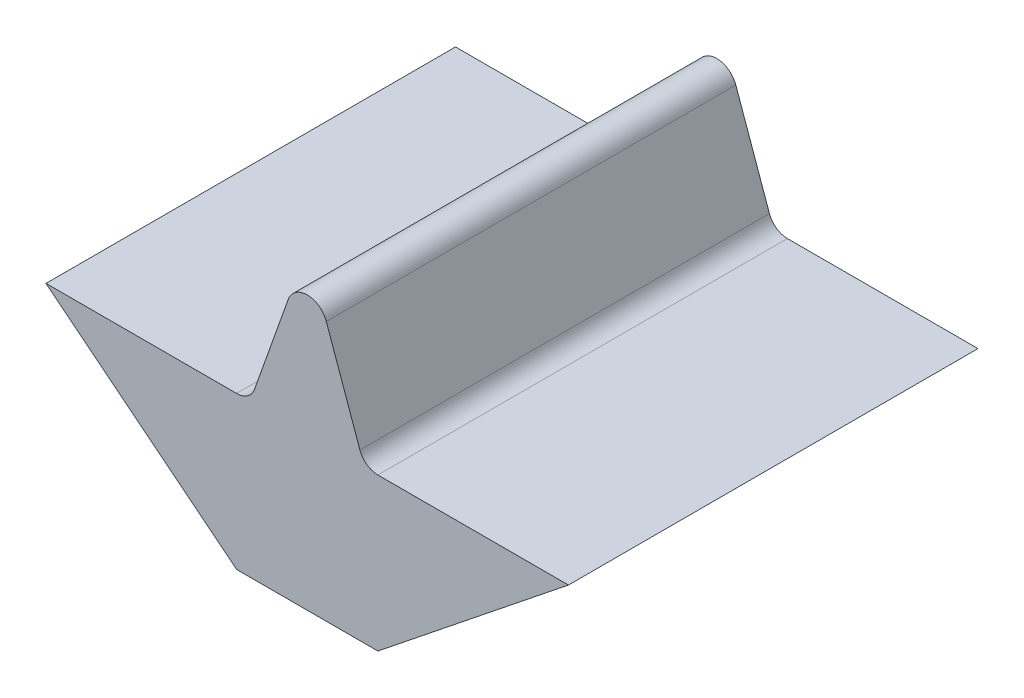
SolidWorks part; units mm, degrees
material "NEOPRENE"
ref_plane "Front Plane" through (0, 0, 0) normal (0, 0, 1) x (1, 0, 0)
ref_plane "Top Plane" through (0, 0, 0) normal (0, 1, 0) x (1, 0, 0)
ref_plane "Right Plane" through (0, 0, 0) normal (1, 0, 0) x (0, 0, -1)
sketch "Sketch1" plane through (0, 0, 0) normal (0, 0, 1) x (1, 0, 0)
  line L0 (401.25, 0) -> (-401.25, 0) construction
  line L1 (401.25, 0) -> (601.25, 200) construction
  line L2 (601.25, 200) -> (-601.25, 200) construction
  line L3 (-601.25, 200) -> (-401.25, 0) construction
  line L4 (-601.25, 283.4375) -> (601.25, 283.4375)
  line L5 (660.2492, 141.0008) -> (460.2492, -58.9992)
  line L6 (-401.25, -83.4375) -> (401.25, -83.4375)
  line L7 (-460.2492, -58.9992) -> (-660.2492, 141.0008)
  line L8 (-601.25, 303.4375) -> (-18.0902, 303.4375) construction
  line L9 (674.3914, 126.8586) -> (474.3914, -73.1414) construction
  line L10 (401.25, -103.4375) -> (-401.25, -103.4375) construction
  line L11 (-474.3914, -73.1414) -> (-674.3914, 126.8586) construction
  line L12 (0, 0) -> (0, 487.9759) construction
  line L13 (-13.618, 306.2014) -> (-5, 323.4375)
  line L15 (5, 323.4375) -> (13.618, 306.2014)
  line L16 (18.0902, 303.4375) -> (601.25, 303.4375) construction
  line L17 (-289.7519, 525.3669) -> (-115.2952, 525.3669)
  arc A0 (-601.25, 283.4375) -> (-660.2492, 141.0008) centre (-601.25, 200) ccw
  arc A1 (660.2492, 141.0008) -> (601.25, 283.4375) centre (601.25, 200) ccw
  arc A2 (401.25, -83.4375) -> (460.2492, -58.9992) centre (401.25, 0) ccw
  arc A3 (-460.2492, -58.9992) -> (-401.25, -83.4375) centre (-401.25, 0) ccw
  arc A5 (-601.25, 303.4375) -> (-674.3914, 126.8586) centre (-601.25, 200) ccw construction
  arc A6 (674.3914, 126.8586) -> (601.25, 303.4375) centre (601.25, 200) ccw construction
  arc A7 (401.25, -103.4375) -> (474.3914, -73.1414) centre (401.25, 0) ccw construction
  arc A8 (-474.3914, -73.1414) -> (-401.25, -103.4375) centre (-401.25, 0) ccw construction
  arc A9 (13.618, 306.2014) -> (18.0902, 303.4375) centre (18.0902, 308.4375) ccw
  arc A10 (-13.618, 306.2014) -> (-18.0902, 303.4375) centre (-18.0902, 308.4375) cw
  arc A11 (-5, 323.4375) -> (5, 323.4375) centre (0, 320.9375) cw
  spline S0 degree 3 poles (18.0902, 303.4375) (212.4768, 303.4375) (413.5359, 303.4375) (621.2675, 303.4375) (641.3554, 296.0526) (653.1688, 289.7122) (658.7168, 286.0051) (694.6034, 262.0265) (711.1202, 222.1515) (702.7, 179.8203) (701.3982, 173.276) (697.5283, 160.4393) (688.5459, 141.0132) (612.4429, 64.9102) (539.4649, -8.0678) (469.612, -77.9208) (464.255, -82.1276) (460.5901, -84.7534) (458.7168, -86.0051) (447.3858, -93.5763) (434.7955, -98.7914) (421.4297, -101.45) (419.2199, -101.8895) (414.7717, -102.6242) (408.0091, -103.4375) (136.003, -103.4375) (-136.003, -103.4375) (-408.0091, -103.4375) (-414.7717, -102.6242) (-419.2199, -101.8895) (-421.4297, -101.45) (-434.7955, -98.7914) (-447.3858, -93.5763) (-458.7168, -86.0051) (-460.5901, -84.7534) (-464.255, -82.1276) (-469.612, -77.9208) (-539.4649, -8.0678) (-612.4429, 64.9102) (-688.5459, 141.0132) (-697.5283, 160.4393) (-701.3982, 173.276) (-702.7, 179.8203) (-711.1202, 222.1515) (-694.6034, 262.0265) (-658.7168, 286.0051) (-653.1688, 289.7122) (-641.3554, 296.0526) (-621.2675, 303.4375) (-413.5359, 303.4375) (-212.4768, 303.4375) (-18.0902, 303.4375) knots 0 0 0 0 0.184171 0.190492 0.196814 0.203136 0.203136 0.203136 0.239434 0.239434 0.239434 0.245756 0.252078 0.258399 0.347725 0.34986 0.351995 0.354129 0.354129 0.354129 0.366875 0.366875 0.366875 0.36901 0.371145 0.373279 0.626721 0.628855 0.63099 0.633125 0.633125 0.633125 0.645871 0.645871 0.645871 0.648005 0.65014 0.652275 0.741601 0.747922 0.754244 0.760566 0.760566 0.760566 0.796864 0.796864 0.796864 0.803186 0.809508 0.815829 1 1 1 1 weights 1 1 1 1 1 1 1 0.887646 0.887646 1 1 1 1 1 1 1 1 1 1 0.98719 0.98719 1 1 1 1 1 1 1 1 1 1 0.98719 0.98719 1 1 1 1 1 1 1 1 1 1 0.887646 0.887646 1 1 1 1 1 1 1
  point P4 (0, 0)
  point P37 (15, 303.4375)
  point P40 (-15, 303.4375)
  dimension "D5" = 166.875
  dimension "D6" = 166.875
  dimension "D7" = 166.875
  dimension "D8" = 166.875
  dimension "D9" = 206.875
  dimension "D10" = 206.875
  dimension "D11" = 206.875
  dimension "D12" = 206.875
  dimension "D13" = 5.5902
  dimension "D16" = 5
  dimension "D18" = 36.1803
  dimension "D1" = 135
  dimension "D2" = 135
  dimension "D3" = 200
  dimension "D4" = 802.5
  dimension "D14" = 10
  dimension "D15" = 10
  dimension "D17" = 30
sketch "Sketch2" plane through (0, 0, 0) normal (0, 0, 1) x (1, 0, 0)
  line L0 (-269.2848, 142.1121) -> (-219.2848, 142.1121)
  line L1 (-214.574, 145.4365) -> (-205.7564, 170.2269)
  line L3 (-195.7564, 170.2269) -> (-186.9388, 145.4365)
  line L4 (-182.228, 142.1121) -> (-132.228, 142.1121)
  line L7 (-269.2848, 142.1121) -> (-219.2848, 102.1121)
  line L8 (-219.2848, 102.1121) -> (-182.228, 102.1121)
  line L9 (-182.228, 102.1121) -> (-132.228, 142.1121)
  arc A0 (-186.9388, 145.4365) -> (-182.228, 142.1121) centre (-182.228, 147.1121) ccw
  arc A1 (-214.574, 145.4365) -> (-219.2848, 142.1121) centre (-219.2848, 147.1121) cw
  arc A2 (-205.7564, 170.2269) -> (-195.7564, 170.2269) centre (-200.7564, 168.4485) cw
  point P9 (-185.7564, 142.1121)
  point P12 (-215.7564, 142.1121)
  dimension "D5" = 5
  dimension "D1" = 10
  dimension "D2" = 10
  dimension "D3" = 10
  dimension "D4" = 50
  dimension "D6" = 50
  dimension "D7" = 0
  dimension "D8" = 0
  dimension "D9" = 40
extrude "Boss-Extrude1" add sketch "Sketch2" along normal blind 107.424
ref_plane "Plane1" through (0, 0, 53.712) normal (0, 0, 1) x (1, 0, 0)
